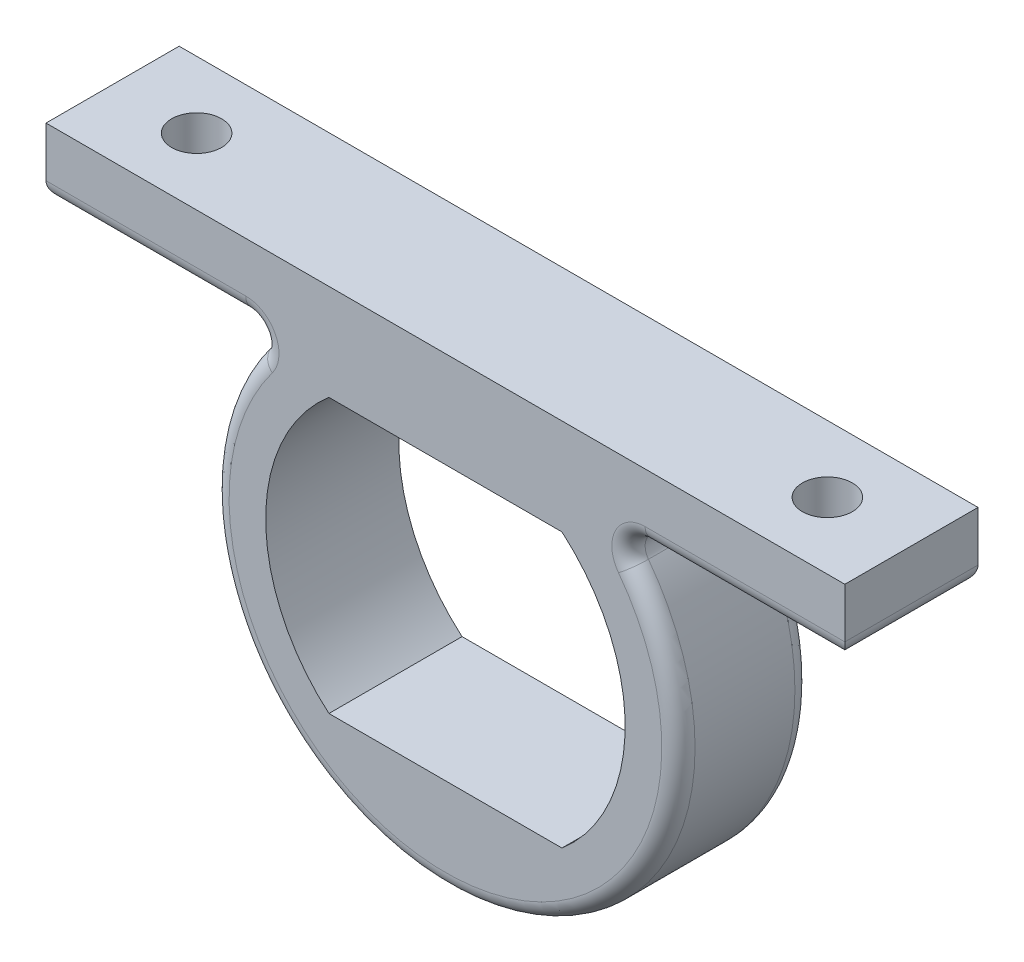
SolidWorks part; units mm, degrees
ref_plane "Alzado" through (0, 0, 0) normal (0, 0, 1) x (1, 0, 0)
ref_plane "Planta" through (0, 0, 0) normal (0, 1, 0) x (1, 0, 0)
ref_plane "Vista lateral" through (0, 0, 0) normal (1, 0, 0) x (0, 0, -1)
sketch "Croquis1" plane through (0, 0, 0) normal (0, 0, 1) x (1, 0, 0)
  line L0 (0, 14) -> (-24, 14)
  line L1 (-24, 14) -> (-24, 10)
  line L2 (-24, 10) -> (-9.798, 10)
  line L3 (0, 14) -> (24, 14)
  line L4 (24, 14) -> (24, 10)
  line L5 (0, -10) -> (0, 10) construction
  line L6 (24, 10) -> (9.798, 10)
  circle A0 centre (0, 0) radius 10
  arc A1 (-9.798, 10) -> (9.798, 10) centre (0, 0) ccw
  dimension "D1" = 20
  dimension "D2" = 48
  dimension "D5" = 24
  dimension "D4" = 4
  dimension "D3" = 14
extrude "Saliente-Extruir1" add sketch "Croquis1" along normal blind 8 contours L4 L6 A1 L2 L1 L0 L3
sketch "Croquis2" plane through (0, 0, 8) normal (0, 0, 1) x (1, 0, 0)
  line L0 (-7, 8.2244) -> (7, 8.2244)
  line L1 (-7, -8.2244) -> (7, -8.2244)
  arc A0 (-7, 8.2244) -> (-7, -8.2244) centre (0, 0) ccw
  arc A1 (7, 8.2244) -> (7, -8.2244) centre (0, 0) cw
  dimension "D1" = 10.8
  dimension "D2" = 14
  dimension "D4" = 10.8
  dimension "D3" = 14
extrude "Cortar-Extruir1" cut sketch "Croquis2" against normal through all
fillet "Redondeo1" radius 1 10 edges at (-16.899, 10, 8) (-16.899, 10, 0) (16.899, 10, 8) (16.899, 10, 0) (-9.798, 10, 4) (0, -14, 8) (9.798, 10, 4) (0, -14, 0) (24, 10, 4) (-24, 10, 4)
sketch "Croquis3" plane through (0, 10, 0) normal (0, -1, 0) x (-1, 0, 0)
  line L0 (23, -7) -> (23, -1) construction
  line L2 (12, -7) -> (23, -7) construction
  line L4 (-23, -7) -> (-12, -7) construction
  line L5 (-23, -1) -> (-23, -7) construction
  circle A0 centre (18.9495, -4) radius 1.5
  circle A1 centre (-18.9495, -4) radius 1.5
  dimension "D1" = 3
  dimension "D2" = 3
  dimension "D3" = 4.0505
  dimension "D4" = 3
  dimension "D5" = 3
  dimension "D6" = 4.0505
extrude "Cortar-Extruir2" cut sketch "Croquis3" against normal through all
